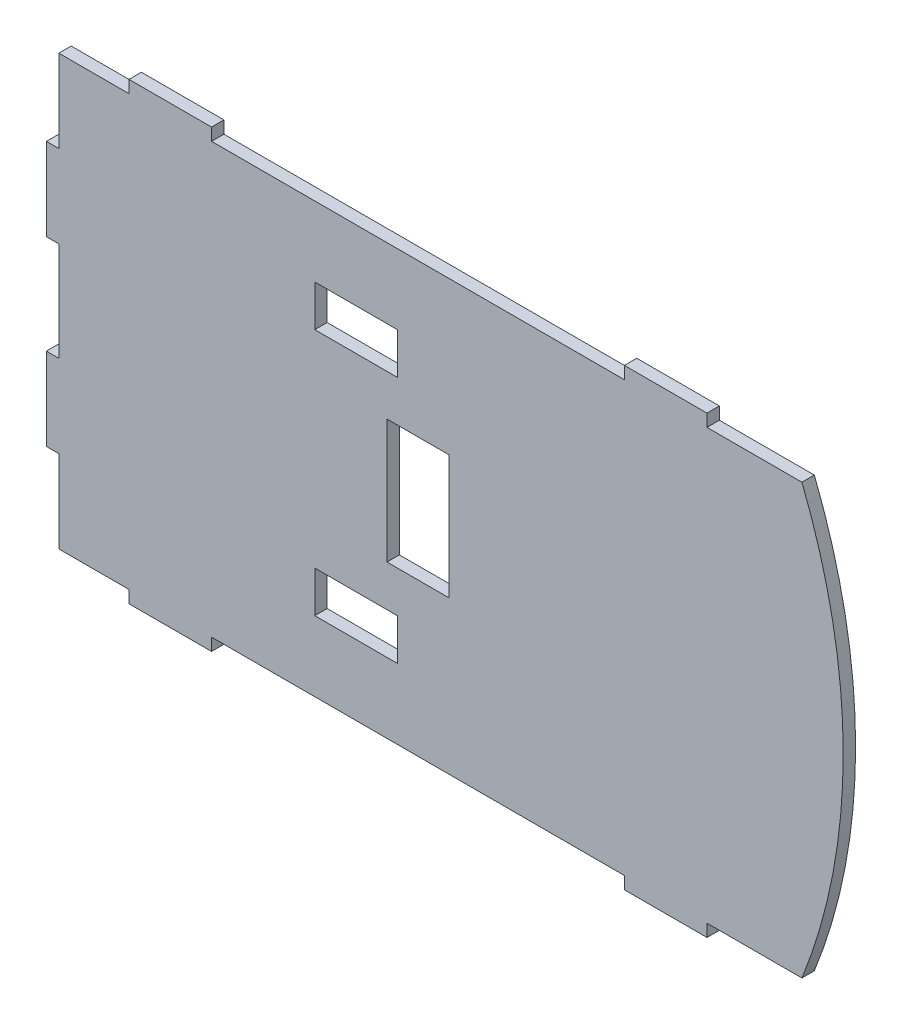
SolidWorks part; units mm, degrees
ref_plane "Front Plane" through (0, 0, 0) normal (0, 0, 1) x (1, 0, 0)
ref_plane "Top Plane" through (0, 0, 0) normal (0, 1, 0) x (1, 0, 0)
ref_plane "Right Plane" through (0, 0, 0) normal (1, 0, 0) x (0, 0, -1)
sketch "Sketch1" plane through (0, 0, 0) normal (0, 0, 1) x (1, 0, 0)
  line L0 (-50, 52) -> (-50, 55)
  line L1 (-87, -52) -> (-70, -52)
  line L2 (-87, -12) -> (-87, 12)
  line L3 (-87, 52) -> (-70, 52)
  line L4 (70, 52) -> (70, 55)
  line L5 (-90, -52) -> (90, 52) construction
  line L6 (-90, 52) -> (90, -52) construction
  line L7 (-7.5, -15) -> (7.5, -15)
  line L8 (-7.5, -15) -> (-7.5, 15)
  line L9 (-7.5, 15) -> (7.5, 15)
  line L10 (7.5, -15) -> (7.5, 15)
  line L11 (-7.5, -15) -> (7.5, 15) construction
  line L12 (-7.5, 15) -> (7.5, -15) construction
  line L13 (-50, 55) -> (-70, 55)
  line L14 (-70, 55) -> (-70, 52)
  line L15 (70, 55) -> (50, 55)
  line L16 (50, 55) -> (50, 52)
  line L17 (103, 0) -> (-87, 0) construction
  line L18 (-87, -12) -> (-90, -12)
  line L19 (70, -52) -> (70, -55)
  line L20 (70, -55) -> (50, -55)
  line L21 (50, -55) -> (50, -52)
  line L22 (-70, -52) -> (-70, -55)
  line L23 (-70, -55) -> (-50, -55)
  line L24 (-50, -55) -> (-50, -52)
  line L25 (-90, 32) -> (-90, 12)
  line L26 (-87, 32) -> (-87, 52)
  line L27 (-5, 35) -> (-25, 35)
  line L28 (-87, -32) -> (-87, -52)
  line L29 (-90, 12) -> (-87, 12)
  line L30 (-5, 35) -> (-5, 25)
  line L31 (90, -52) -> (93, -52)
  line L32 (90, 52) -> (93, 52)
  line L33 (-50, -52) -> (50, -52)
  line L34 (70, -52) -> (90, -52)
  line L35 (70, 52) -> (90, 52)
  line L36 (-50, 52) -> (50, 52)
  line L37 (-87, -32) -> (-90, -32)
  line L38 (-5, 25) -> (-25, 25)
  line L39 (-90, -12) -> (-90, -32)
  line L40 (-87, 32) -> (-90, 32)
  line L41 (-25, 35) -> (-25, 25)
  line L42 (-5, 35) -> (-25, 25) construction
  line L43 (-5, 25) -> (-25, 35) construction
  line L44 (-5, -35) -> (-25, -25) construction
  line L45 (-5, -25) -> (-25, -35) construction
  line L46 (-25, -35) -> (-25, -25)
  line L47 (-5, -35) -> (-25, -35)
  line L48 (-5, -35) -> (-5, -25)
  line L49 (-5, -25) -> (-25, -25)
  arc A0 (93, 52) -> (93, -52) centre (-37.2, 0) cw
  point P0 (0, 0)
  point P6 (0, 0)
  point P31 (-15, 30)
  point P44 (103, 0)
  dimension "D2" = 20
  dimension "D3" = 15
  dimension "D4" = 30
  dimension "D5" = 87
  dimension "D6" = 20
  dimension "D7" = 20
  dimension "D8" = 20
  dimension "D9" = 20
  dimension "D10" = 3
  dimension "D11" = 20
  dimension "D12" = 20
  dimension "D13" = 3
  dimension "D14" = 20
  dimension "D15" = 3
  dimension "D16" = 75
  dimension "D17" = 30
  dimension "D18" = 20
  dimension "D19" = 20
  dimension "D20" = 10
extrude "Boss-Extrude1" add sketch "Sketch1" along normal blind 3
